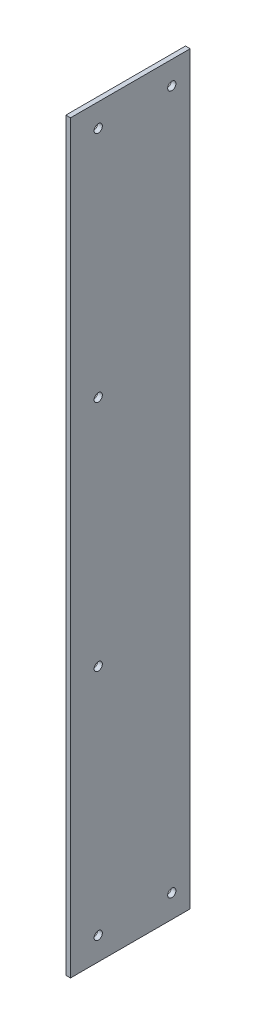
SolidWorks part; units mm, degrees
ref_plane "Front Plane" through (0, 0, 0) normal (1, 0, 0) x (0, 1, 0)
ref_plane "Top Plane" through (0, 0, 0) normal (0, 0, 1) x (0, 1, 0)
ref_plane "Right Plane" through (0, 0, 0) normal (0, 1, 0) x (-1, 0, 0)
sketch "Sketch1" plane through (0, 0, 0) normal (1, 0, 0) x (0, 1, 0)
  line L1 (250, -37.5) -> (-250, -37.5)
  line L2 (250, -37.5) -> (250, 37.5)
  line L3 (250, 37.5) -> (-250, 37.5)
  line L4 (-250, -37.5) -> (-250, 37.5)
  line L5 (250, -37.5) -> (-250, 37.5) construction
  line L6 (250, 37.5) -> (-250, -37.5) construction
  circle A0 centre (-237.5, 25) radius 2.8
  circle A1 centre (-79.1667, 25) radius 2.8
  circle A2 centre (79.1667, 25) radius 2.8
  circle A3 centre (237.5, 25) radius 2.8
  circle A4 centre (-79.1667, -25) radius 2.8
  circle A5 centre (79.1667, -25) radius 2.8
  circle A6 centre (237.5, -25) radius 2.8
  circle A7 centre (-237.5, -25) radius 2.8
  point P0 (0, 0)
  dimension "D5" = 5.6
  dimension "D1" = 500
  dimension "D2" = 75
  dimension "D3" = 12.5
  dimension "D4" = 12.5
  dimension "D6" = 4
  dimension "D7" = 2
extrude "Boss-Extrude1" add sketch "Sketch1" along normal blind 3.175 contours L4 L1 L2 L3 A7 A6 A5 A4 A3 A2 A1 A0 | A4 | A5
sketch "Sketch2" plane through (3.175, 0, 0) normal (1, 0, 0) x (0, 1, 0)
  line L1 (-250, -37.5) -> (-253.175, -37.5)
  line L2 (-250, -37.5) -> (-250, 43.85)
  line L3 (-250, 43.85) -> (-253.175, 43.85)
  line L4 (-253.175, -37.5) -> (-253.175, 43.85)
  line L5 (-250, -37.5) -> (-253.175, 43.85) construction
  line L6 (-250, 43.85) -> (-253.175, -37.5) construction
  line L7 (250, -37.5) -> (253.175, -37.5)
  line L8 (250, -37.5) -> (250, 43.85)
  line L9 (250, 43.85) -> (253.175, 43.85)
  line L10 (253.175, -37.5) -> (253.175, 43.85)
  line L11 (250, -37.5) -> (253.175, 43.85) construction
  line L12 (250, 43.85) -> (253.175, -37.5) construction
  line L13 (250, 43.85) -> (-250, 43.85)
  line L14 (250, 43.85) -> (250, 37.5)
  line L15 (250, 37.5) -> (-250, 37.5)
  line L16 (-250, 43.85) -> (-250, 37.5)
  line L17 (250, 43.85) -> (-250, 37.5) construction
  line L18 (250, 37.5) -> (-250, 43.85) construction
  point P2 (250, 66.2363)
  point P4 (-251.5875, 3.175)
  point P10 (251.5875, 3.175)
  point P15 (0, 40.675)
  point P17 (0, 0)
  line M19 (-250, 37.5) -> (-250, -37.5)
  line M21 (250, -37.5) -> (250, 37.5)
  line M22 (250, 37.5) -> (-250, 37.5)
  dimension "D1" = 6.35
  dimension "D2" = 3.175
  dimension "D3" = 3.175
extrude "Boss-Extrude2" add sketch "Sketch2" against normal through all contours L4 L1 L2 L3 M19 | L8 L13 L2 M22 | L7 L10 L9 L8 M21
